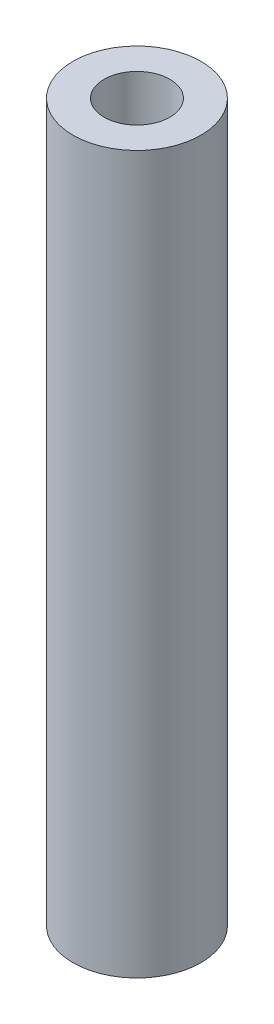
SolidWorks part; units mm, degrees
ref_plane "Front" through (0, 0, 0) normal (0, 0, 1) x (1, 0, 0)
ref_plane "Top" through (0, 0, 0) normal (0, 1, 0) x (1, 0, 0)
ref_plane "Right" through (0, 0, 0) normal (1, 0, 0) x (0, 0, -1)
sketch "Sketch1" plane through (0, 0, 0) normal (0, 1, 0) x (1, 0, 0)
  circle A0 centre (0, 0) radius 3.175
  dimension "D1" = 6.35
extrude "Boss-Extrude1" add sketch "Sketch1" along normal blind 35.56
sketch "Sketch2" plane through (0, 35.56, 0) normal (0, 1, 0) x (1, 0, 0)
  circle A0 centre (0, 0) radius 1.632
  dimension "D1" = 3.2639
extrude "Cut-Extrude1" cut sketch "Sketch2" against normal through all
